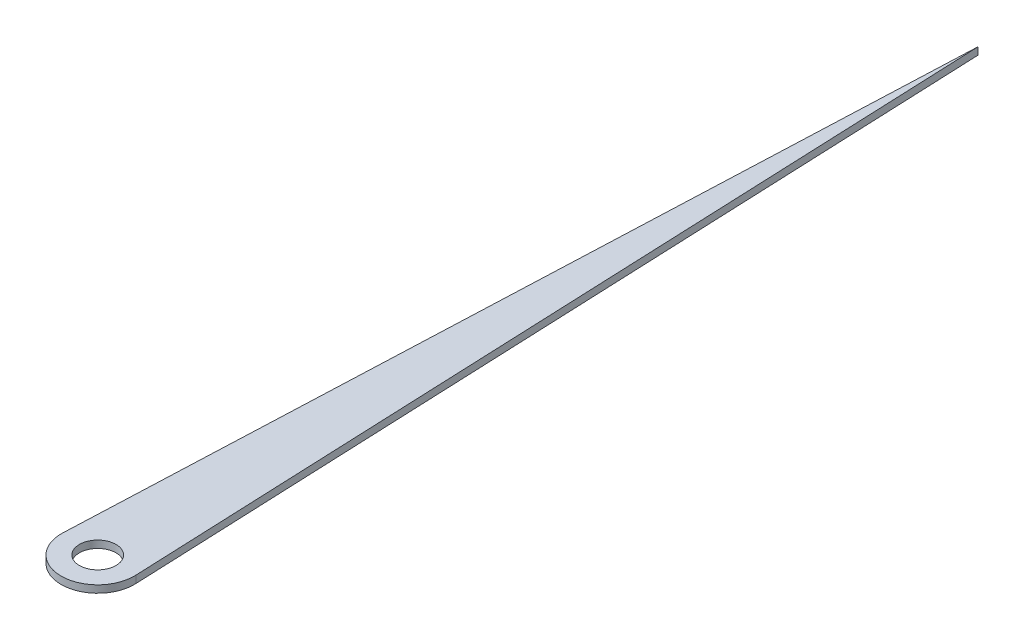
SolidWorks part; units mm, degrees
ref_plane "Front Plane" through (0, 0, 0) normal (0, 0, 1) x (1, 0, 0)
ref_plane "Top Plane" through (0, 0, 0) normal (0, 1, 0) x (1, 0, 0)
ref_plane "Right Plane" through (0, 0, 0) normal (1, 0, 0) x (0, 0, -1)
sketch "Sketch2" plane through (0, 0, 0) normal (0, 1, 0) x (1, 0, 0)
  line L0 (1.3718, 0.1094) -> (1.3718, 30.6594) construction
  line L1 (1.3718, 30.6594) -> (0.1029, 0.1622)
  line L2 (2.6407, 0.1622) -> (1.3718, 30.6594)
  circle A0 centre (1.3718, 0.1094) radius 1.27
  circle A1 centre (1.3718, 0.1094) radius 0.635
  dimension "D1" = 1.27
  dimension "D2" = 2.54
extrude "Boss-Extrude2" add sketch "Sketch2" along normal blind 0.254
